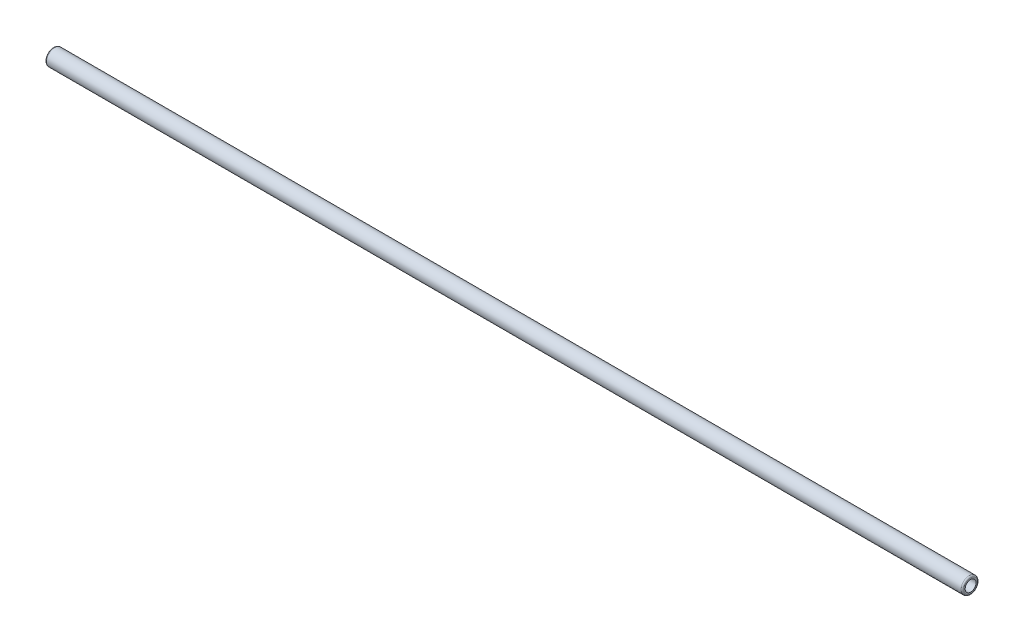
SolidWorks part; units mm, degrees
ref_plane "Спереди" through (0, 0, 0) normal (0, 0, 1) x (1, 0, 0)
ref_plane "Сверху" through (0, 0, 0) normal (0, 1, 0) x (1, 0, 0)
ref_plane "Справа" through (0, 0, 0) normal (1, 0, 0) x (0, 0, -1)
other "Configuration Table"
sketch "Эскиз1" plane through (0, 0, 0) normal (1, 0, 0) x (0, 0, -1)
  circle A0 centre (0, 0) radius 2
  circle A1 centre (0, 0) radius 3
  dimension "D1" = 6
  dimension "D2" = 4
extrude "Бобышка-Вытянуть1" add sketch "Эскиз1" along normal mid plane 336
fillet "Скругление1" radius 0.5 2 edges at (-168, 0, -3) (168, 0, -3)
